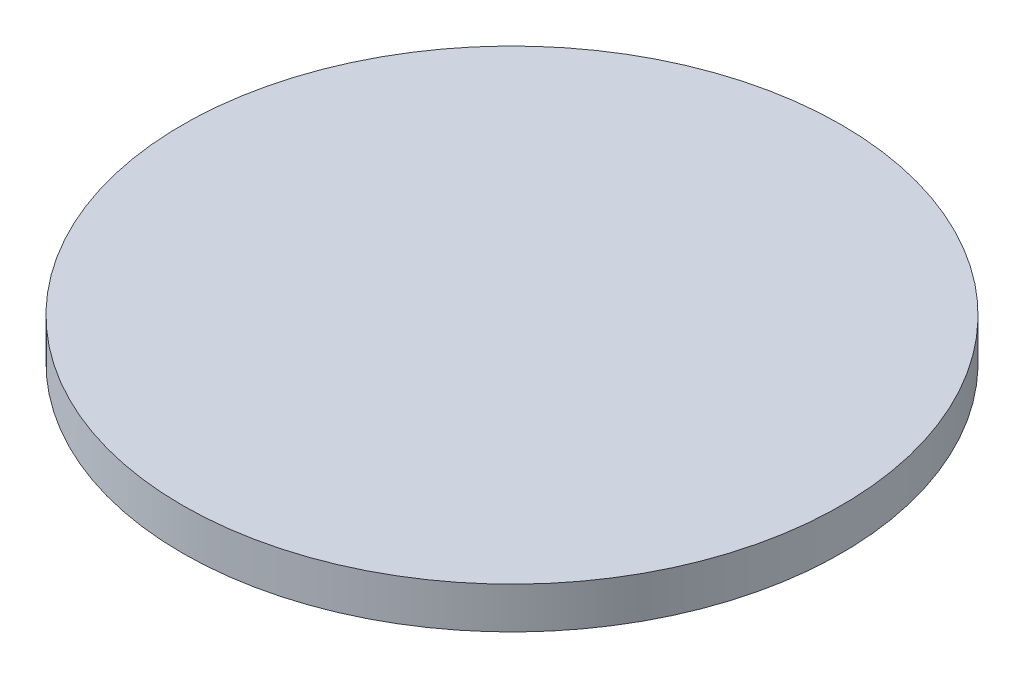
SolidWorks part; units mm, degrees
ref_plane "Front Plane" through (0, 0, 0) normal (0, 0, 1) x (1, 0, 0)
ref_plane "Top Plane" through (0, 0, 0) normal (0, 1, 0) x (1, 0, 0)
ref_plane "Right Plane" through (0, 0, 0) normal (1, 0, 0) x (0, 0, -1)
sketch "Sketch1" plane through (0, 0, 0) normal (0, 1, 0) x (1, 0, 0)
  circle A0 centre (0, 0) radius 20.2176
  dimension "D1" = 40.4352
extrude "Boss-Extrude1" add sketch "Sketch1" along normal blind 2.54
